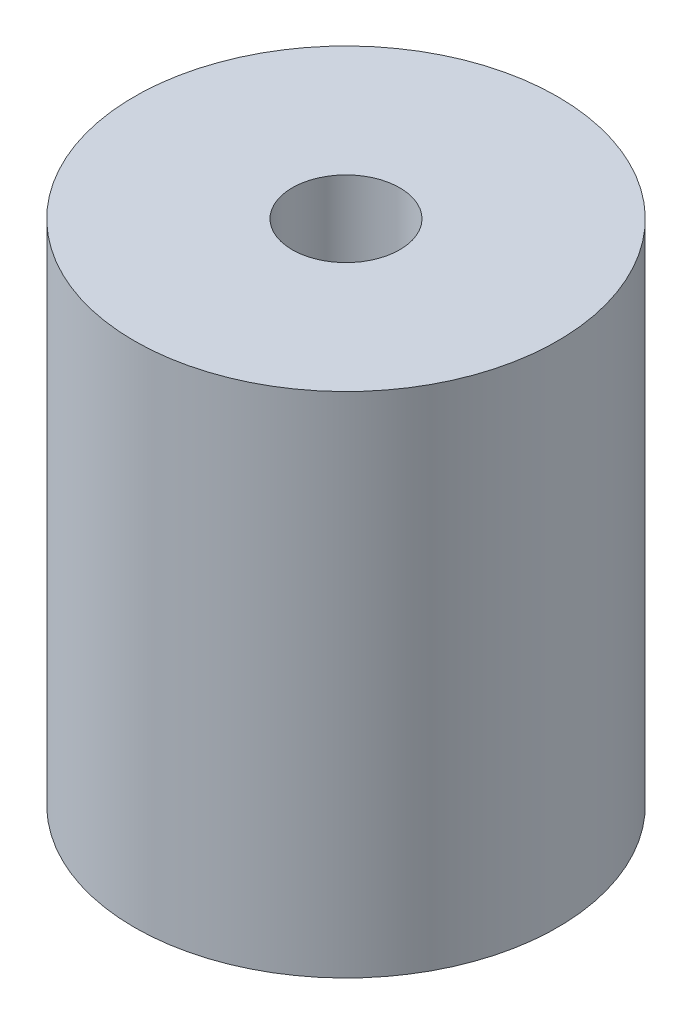
SolidWorks part; units mm, degrees
material "Stainless Steel (ferritic)"
ref_plane "Front Plane" through (0, 0, 0) normal (0, 0, 1) x (1, 0, 0)
ref_plane "Top Plane" through (0, 0, 0) normal (0, 1, 0) x (1, 0, 0)
ref_plane "Right Plane" through (0, 0, 0) normal (1, 0, 0) x (0, 0, -1)
sketch "Sketch1" plane through (0, 0, 0) normal (0, 1, 0) x (1, 0, 0)
  circle A0 centre (0, 0) radius 12.5
  dimension "D1" = 25
extrude "Boss-Extrude1" add sketch "Sketch1" along normal blind 30
sketch "Sketch2" plane through (0, 30, 0) normal (0, 1, 0) x (1, 0, 0)
  circle A0 centre (0, 0) radius 3.175
  dimension "D1" = 6.35
extrude "Cut-Extrude1" cut sketch "Sketch2" against normal blind 12
sketch "Sketch3" plane through (0, 0, 0) normal (0, -1, 0) x (1, 0, 0)
  circle A0 centre (0, 0) radius 4
  dimension "D1" = 8
extrude "Cut-Extrude2" cut sketch "Sketch3" against normal blind 12
